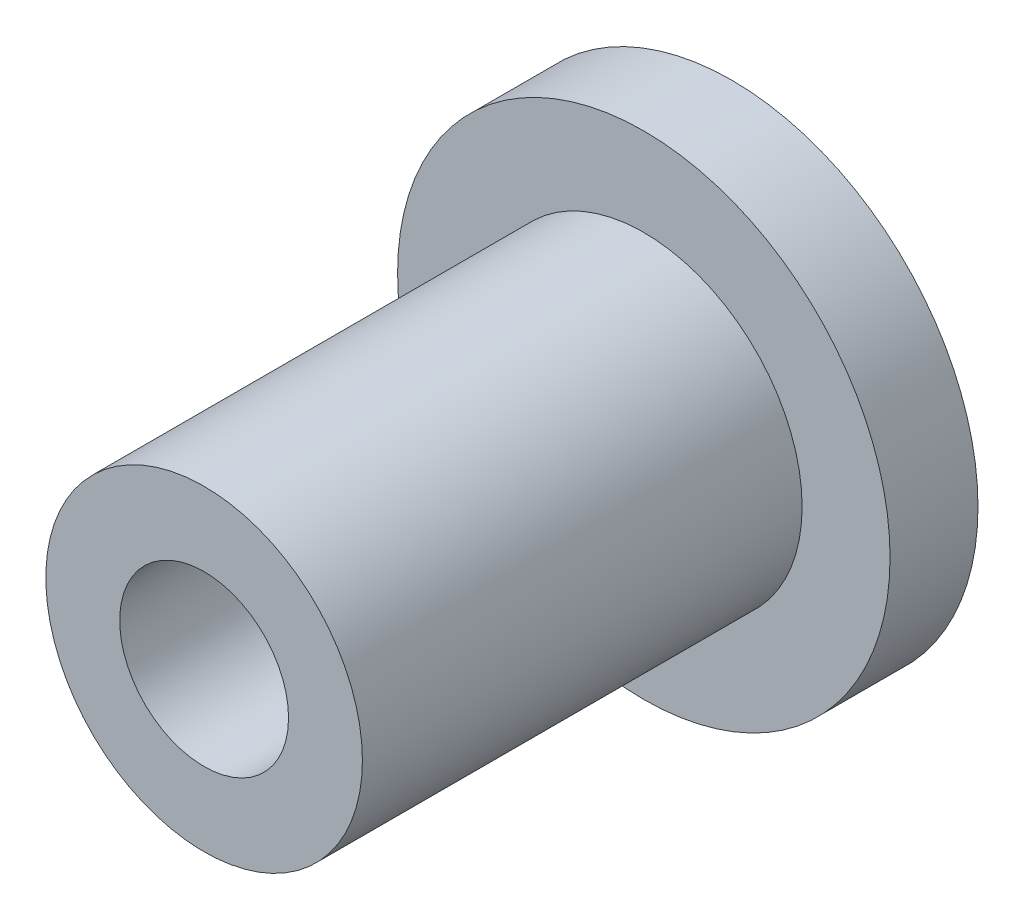
SolidWorks part; units mm, degrees
ref_plane "前视基准面" through (0, 0, 0) normal (0, 0, 1) x (1, 0, 0)
ref_plane "上视基准面" through (0, 0, 0) normal (0, 1, 0) x (1, 0, 0)
ref_plane "右视基准面" through (0, 0, 0) normal (1, 0, 0) x (0, 0, -1)
other "Configuration Table"
sketch "Sketch1" plane through (0, 0, 0) normal (0, 0, 1) x (1, 0, 0)
  circle A0 centre (0, 0) radius 7
  dimension "14" = 14
extrude "Boss-Extrude1" add sketch "Sketch1" along normal blind 2.5
sketch "Sketch2" plane through (0, 0, 2.5) normal (0, 0, 1) x (1, 0, 0)
  circle A0 centre (0, 0) radius 4.5
  dimension "D1" = 9
extrude "Boss-Extrude2" add sketch "Sketch2" along normal blind 12.5
sketch "Sketch3" plane through (0, 0, 15) normal (0, 0, 1) x (1, 0, 0)
  circle A5 centre (0, 0) radius 2.4
  dimension "D1" = 4.8
extrude "Cut-Extrude1" cut sketch "Sketch3" against normal blind 5
